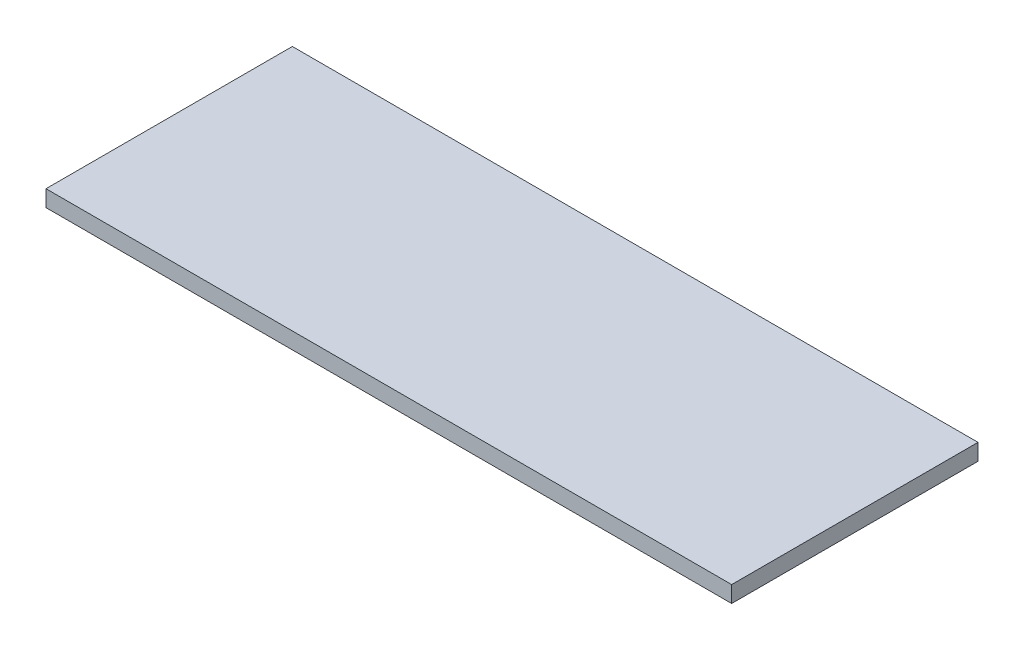
SolidWorks part; units mm, degrees
ref_plane "Piano frontale" through (0, 0, 0) normal (0, 0, 1) x (1, 0, 0)
ref_plane "Piano superiore" through (0, 0, 0) normal (0, 1, 0) x (1, 0, 0)
ref_plane "Piano destro" through (0, 0, 0) normal (1, 0, 0) x (0, 0, -1)
sketch "Schizzo1" plane through (0, 0, 0) normal (0, 1, 0) x (1, 0, 0)
  line L1 (78.5, -25) -> (-78.5, -25) construction
  line L2 (78.5, -25) -> (78.5, 25) construction
  line L3 (78.5, 25) -> (-78.5, 25) construction
  line L4 (-78.5, -25) -> (-78.5, 25) construction
  line L5 (0, -55) -> (0, 55) construction
  line L6 (83.5, 30) -> (-83.5, 30)
  line L7 (83.5, 30) -> (83.5, -30)
  line L8 (83.5, -30) -> (-83.5, -30)
  line L9 (-83.5, 30) -> (-83.5, -30)
  line L10 (-55, 0) -> (55, 0) construction
  point P10 (0, 30)
  point P11 (83.5, 0)
  point P14 (-78.5, 0)
  point P15 (0, -25)
  dimension "D1" = 157
  dimension "D2" = 50
  dimension "D3" = 5
  dimension "D4" = 5
extrude "Estrusione-Estrusione1" add sketch "Schizzo1" along normal blind 4
